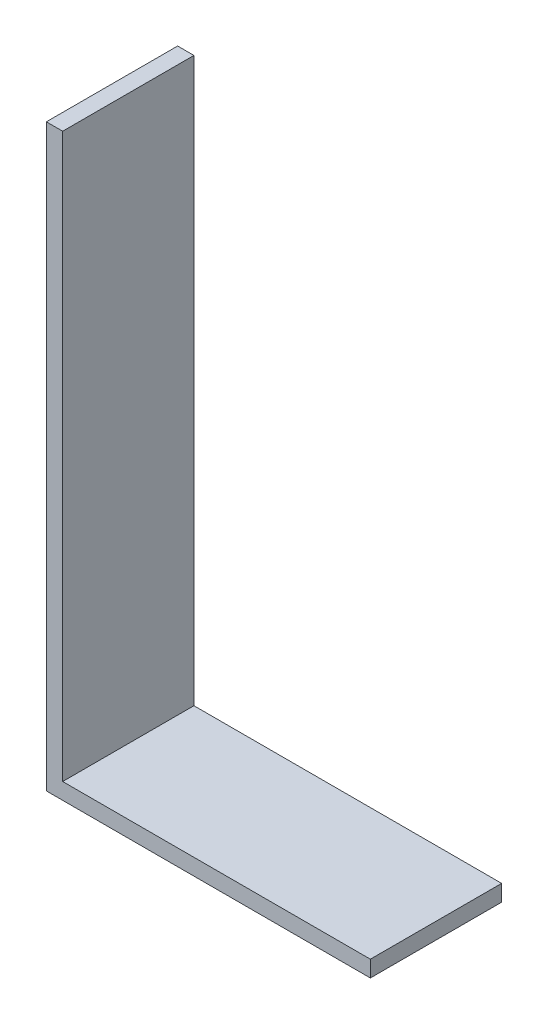
SolidWorks part; units mm, degrees
ref_plane "Alzado" through (0, 0, 0) normal (0, 0, 1) x (1, 0, 0)
ref_plane "Planta" through (0, 0, 0) normal (0, 1, 0) x (1, 0, 0)
ref_plane "Vista lateral" through (0, 0, 0) normal (1, 0, 0) x (0, 0, -1)
sketch "Croquis1" plane through (0, 0, 0) normal (0, 0, 1) x (1, 0, 0)
  line L0 (125.365, 6.31) -> (125.365, 0)
  line L1 (125.365, 0) -> (0, 0)
  line L2 (0, 0) -> (0, 224.2163)
  line L3 (0, 224.2163) -> (6.31, 224.2163)
  line L4 (6.31, 224.2163) -> (6.31, 6.31)
  line L5 (6.31, 6.31) -> (125.365, 6.31)
  point P6 (0, 0)
  dimension "D1" = 224.2163
  dimension "D2" = 125.365
  dimension "D3" = 6.31
  dimension "D4" = 6.31
extrude "Saliente-Extruir1" add sketch "Croquis1" along normal blind 50.8
